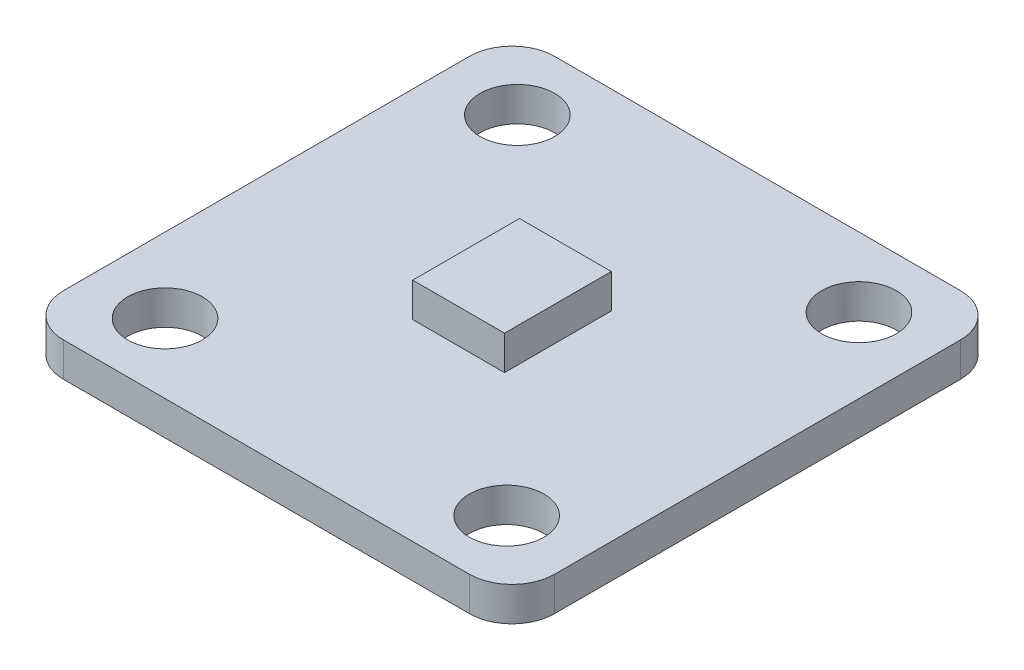
SolidWorks part; units mm, degrees
ref_plane "Front Plane" through (0, 0, 0) normal (0, 0, 1) x (1, 0, 0)
ref_plane "Top Plane" through (0, 0, 0) normal (0, 1, 0) x (1, 0, 0)
ref_plane "Right Plane" through (0, 0, 0) normal (1, 0, 0) x (0, 0, -1)
sketch "Sketch1" plane through (0, 0, 0) normal (0, 1, 0) x (1, 0, 0)
  line L1 (-11.5, 11.5) -> (11.5, 11.5)
  line L2 (-11.5, 11.5) -> (-11.5, -11.5)
  line L3 (-11.5, -11.5) -> (11.5, -11.5)
  line L4 (11.5, 11.5) -> (11.5, -11.5)
  line L5 (-11.5, 11.5) -> (11.5, -11.5) construction
  line L6 (-11.5, -11.5) -> (11.5, 11.5) construction
  point P0 (0, 0)
  dimension "D1" = 23
extrude "Boss-Extrude1" add sketch "Sketch1" along normal blind 1.6
fillet "Fillet1" radius 2 4 edges at (-11.5, 0.8, -11.5) (11.5, 0.8, -11.5) (11.5, 0.8, 11.5) (-11.5, 0.8, 11.5)
sketch "Sketch2" plane through (0, 1.6, 0) normal (0, 1, 0) x (1, 0, 0)
  line L0 (9.5, 11.5) -> (-9.5, 11.5) construction
  line L1 (-11.5, 9.5) -> (-11.5, -9.5) construction
  line L2 (0, 11.5) -> (0, -11.5) construction
  line L3 (-9.5, -11.5) -> (9.5, -11.5) construction
  line L4 (-11.5, 0) -> (11.5, 0) construction
  line L5 (11.5, -9.5) -> (11.5, 9.5) construction
  circle A0 centre (-8, 8.25) radius 1.75
  circle A4 centre (8, 8.25) radius 1.75
  circle A5 centre (8, -8.25) radius 1.75
  circle A6 centre (-8, -8.25) radius 1.75
  point P8 (-8, 10)
  point P9 (-9.75, 8.25)
  dimension "D1" = 3.5
  dimension "D2" = 1.5
  dimension "D3" = 1.75
extrude "Cut-Extrude1" cut sketch "Sketch2" against normal up to next
sketch "Sketch3" plane through (0, 1.6, 0) normal (0, 1, 0) x (1, 0, 0)
  line L1 (-2.15, 2.5) -> (2.15, 2.5)
  line L2 (-2.15, 2.5) -> (-2.15, -2.5)
  line L3 (-2.15, -2.5) -> (2.15, -2.5)
  line L4 (2.15, 2.5) -> (2.15, -2.5)
  line L5 (-2.15, 2.5) -> (2.15, -2.5) construction
  line L6 (-2.15, -2.5) -> (2.15, 2.5) construction
  point P0 (0, 0)
  dimension "D1" = 4.3
  dimension "D2" = 5
extrude "Boss-Extrude2" add sketch "Sketch3" along normal blind 1.6
